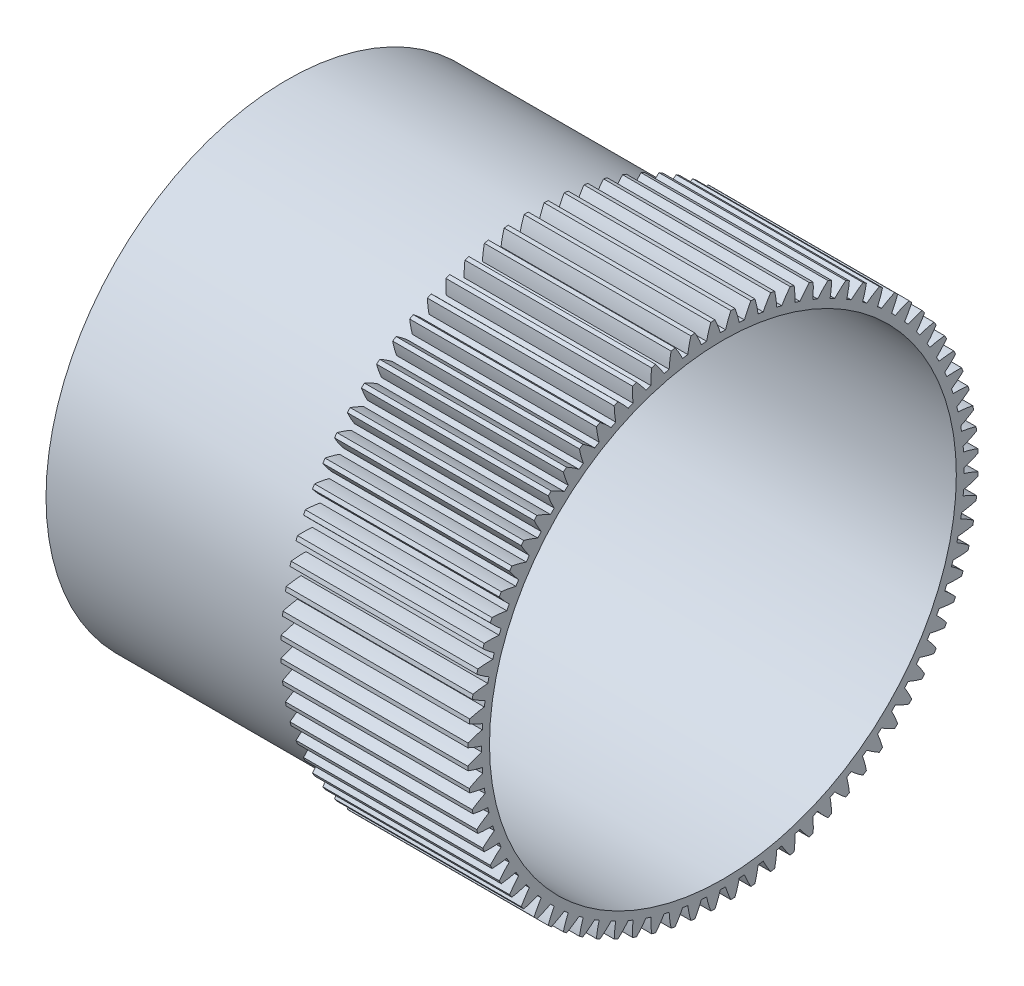
SolidWorks part; units mm, degrees
ref_plane "Plane1" through (0, 0, 0) normal (0, 0, 1) x (1, 0, 0)
ref_plane "Plane2" through (0, 0, 0) normal (0, 1, 0) x (1, 0, 0)
ref_plane "Plane3" through (0, 0, 0) normal (1, 0, 0) x (0, 0, -1)
other "Configuration Table"
sketch "HoldingSke" plane through (0, 0, 0) normal (0, 1, 0) x (1, 0, 0)
  line L0 (0, 0) -> (0.3473, -1.9696)
  line L1 (-15, 0) -> (100, 0) construction
  line L2 (0, 0) -> (-2.1039, 2.3779)
  line L3 (0, 0) -> (-11.863, 4.5341)
  line L4 (0, 0) -> (1.4996, 8.5048)
  line L5 (0, 0) -> (-46.8476, -17.4728)
  line L6 (0, 0) -> (-2.8599, -1.9296)
  line L7 (-2.1039, 2.3779) -> (8.6589, 51.2073)
  line L8 (-76.2, 54.61) -> (-76.1, 54.61)
  line L9 (-71.009, 38.7566) -> (-53.1078, 45.2721)
  line L10 (-76.2, 71.12) -> (104.1128, 71.12)
  line L11 (0, 0) -> (-3.45, 0)
  line L12 (-76.2, 101.6) -> (-76.181, 101.6)
  line L13 (24.9733, 27.94) -> (52.9518, 28.4284)
  line L14 (24.9733, 27.94) -> (24.9743, 27.94)
  line L15 (24.9733, 27.94) -> (100.4006, 29.5858)
  line L16 (-63.627, -0.5) -> (-12.827, -0.5)
  circle A0 centre (0, 0) radius 0.5
  circle A1 centre (0, 0) radius 19.374
  circle A2 centre (0, 0) radius 37.5
  circle A3 centre (0, 0) radius 0.5
  dimension "MHD" = 38.748
  dimension "Hub_dia" = 75
  dimension "Bore" = 1
  dimension "MBD" = 1
  dimension "Num_teeth" = 80
  dimension "Pitch" = 2
  dimension "Overall_len" = 50
  dimension "Show_teeth" = 80
  dimension "Thickness" = 3.45
  dimension "OAL" = 50.0015
  dimension "T_dim" = 0.1
  dimension "Ap" = 20
  dimension "H" = 19.05
  dimension "Pitch_radius" = 180.3128
  dimension "Width" = 3.45
  dimension "Backlash" = 0.019
  dimension "Addendum_fac" = 1
  dimension "Dedendum_fac" = 1.25
  dimension "Clearance_fac" = 0.25
  dimension "Dedendum_add" = 0.001
  dimension "Module" = 0.5
sketch "BasProSke" plane through (0, 0, 0) normal (0, 1, 0) x (1, 0, 0)
  line L0 (-10, 0) -> (60, 0) construction
  line L1 (0, 0) -> (0, 20.5)
  line L2 (0, 0) -> (15, 0)
  line L3 (15, 0) -> (15, 20.5)
  line L4 (15, 20.5) -> (0, 20.5)
  dimension "Thickness" = 15
  dimension "Diameter" = 41
revolve "Base-Revolve" add sketch "BasProSke" angle 360 about L0
sketch "TooCutSke" plane through (0, 0, 0) normal (1, 0, 0) x (0, 0, -1)
  line L1 (0, 0) -> (0, 107) construction
  line L2 (0, 0) -> (-0.4259, 19.9955) construction
  line L3 (0, 0) -> (-1.5701, 39.9627) construction
  line L4 (-0.4259, 19.9955) -> (-0.7851, 19.9814) construction
  arc A0 (0.2101, 19.3729) -> (-0.2101, 19.3729) centre (0, 0) ccw
  arc A1 (0.6519, 20.515) -> (-0.6519, 20.515) centre (0, 0) ccw
  circle A2 centre (0, 0) radius 20 construction
  circle A3 centre (0, 0) radius 18.7939 construction
  arc A4 (-0.2101, 19.3729) -> (-0.6519, 20.515) centre (-7.8705, 17.0665) ccw
  arc A5 (0.6519, 20.515) -> (0.2101, 19.3729) centre (7.8705, 17.0665) ccw
  dimension "Root_dia" = 38.748
  dimension "Overcut_dia" = 41.0508
  dimension "Pitch_dia" = 40
  dimension "Base_dia" = 37.5877
  dimension "Flank_rad" = 8
  dimension "Half_ang" = 2.25
  dimension "Half_CT" = 0.3594
extrude "ToothCut" cut sketch "TooCutSke" along normal through all
fillet "Breaks" [suppressed] radius 0.01
fillet "RootFillets" [suppressed] radius 0.126
pattern_circular "TeethCuts" count 80 every 4.5 about axis through (-10, 0, 0) along (1, 0, 0) of "ToothCut", "RootFillets", "Breaks"
sketch "HubNeaOneSke" plane through (0, 0, 0) normal (-1, 0, 0) x (0, 0, 1)
  circle A0 centre (0, 0) radius 19.374
  dimension "Diameter" = 38.748
extrude "HubNearOne" [suppressed] add sketch "HubNeaOneSke" along normal blind 35.0015
sketch "HubNeaBotSke" plane through (0, 0, 0) normal (-1, 0, 0) x (0, 0, 1)
  circle A0 centre (0, 0) radius 19.374
  dimension "Diameter" = 38.748
extrude "HubNearBoth" [suppressed] add sketch "HubNeaBotSke" along normal blind 17.5008
ref_plane "FarPln" through (15, 0, 0) normal (1, 0, 0) x (0, 0, -1)
sketch "HubFarSke" plane through (15, 0, 0) normal (1, 0, 0) x (0, 0, -1)
  circle A0 centre (0, 0) radius 19.374
  dimension "Diameter" = 38.748
extrude "HubFar" [suppressed] add sketch "HubFarSke" along normal blind 17.5008
sketch "BorSke" plane through (0, 0, 0) normal (1, 0, 0) x (0, 0, -1)
  circle A0 centre (0, 0) radius 0.5
  dimension "Diameter" = 1
extrude "Bore" cut sketch "BorSke" along normal mid plane 100.003
sketch "KeySke" plane through (0, 0, 0) normal (1, 0, 0) x (0, 0, -1)
  line L0 (-0.05, 0) -> (-0.05, 0.6)
  line L1 (-0.05, 0.6) -> (0.05, 0.6)
  line L2 (0.05, 0.6) -> (0.05, 0)
  line L3 (0, 0) -> (0, 34) construction
  line L4 (-0.05, 0) -> (0.05, 0)
  dimension "Offset" = 0.6
  dimension "Width" = 0.1
extrude "Keyway" [suppressed] cut sketch "KeySke" along normal mid plane 100.003
pattern_circular "Keyway2" [suppressed] count 2 every 90 about axis through (-10, 0, 0) along (1, 0, 0)
sketch "Sketch1" plane through (15, 0, 0) normal (1, 0, 0) x (0, 0, -1)
  circle A0 centre (0, 0) radius 18.75
  dimension "D1" = 37.5
extrude "Cut-Extrude1" cut sketch "Sketch1" against normal through all
sketch "Sketch4" plane through (0, 0, 0) normal (-1, 0, 0) x (0, 0, 1)
  circle A0 centre (0, 0) radius 18.75
  circle A1 centre (0, 0) radius 19.374
  arc A2 (17.3567, 8.6079) -> (17.1659, 8.9823) centre (0, 0) ccw construction
  circle A3 centre (0, 0) radius 18.75 construction
extrude "Boss-Extrude5" add sketch "Sketch4" along normal blind 20
sketch "Sketch5" plane through (-20, 0, 0) normal (-1, 0, 0) x (0, 0, 1)
  circle A0 centre (0, 0) radius 18.75
  circle A1 centre (0, 0) radius 18.75 construction
extrude "Boss-Extrude6" add sketch "Sketch5" against normal blind 1
sketch "Sketch6" plane through (-20, 0, 0) normal (-1, 0, 0) x (0, 0, 1)
  circle A0 centre (0, 0) radius 2.45
  dimension "D1" = 4.9
extrude "Boss-Extrude7" add sketch "Sketch6" along normal blind 10
equation "' \"Module@HoldingSke\" = 6.35"
equation "' \"Num_teeth@HoldingSke\" = 12"
equation "' \"Ap@HoldingSke\" =  20"
equation "' \"Ap@HoldingSke\" = 20"
equation "' \"Width@HoldingSke\" = 0.5 * 25.4"
equation "' \"Hub_dia@HoldingSke\"= 1 * 25.4"
equation "' \"Hub_dia@HoldingSke\" = 1 * 25.4"
equation "' \"Overall_len@HoldingSke\" = 1.0 * 25.4"
equation "' \"Bore@HoldingSke\" = 0.75 * 25.4"
equation "' \"T_dim@HoldingSke\" = 0.1 * 25.4"
equation "' \"Width@KeySke\" = 0.25 * 25.4"
equation "' \"Show_teeth@HoldingSke\" = 13"
equation "' \"Backlash@HoldingSke\" = 0.009 * 25.4"
equation "' \"Addendum_fac@HoldingSke\" = 1.0"
equation "' \"Dedendum_fac@HoldingSke\" = 1.25"
equation "' \"Dedendum_add@HoldingSke\" = 0.00005 * 25.4"
equation "' \"Clearance_fac@HoldingSke\" = 0.25"
equation "\"Pitch@HoldingSke\" = 1 / \"Module@HoldingSke\""
equation "\"Overcut_dia@TooCutSke\" = (\"Num_teeth@HoldingSke\" + 2 * \"Addendum_fac@HoldingSke\") / \"Pitch@HoldingSke\" + 0.002 * 25.4"
equation "\"Pitch_dia@TooCutSke\" = \"Num_teeth@HoldingSke\" / \"Pitch@HoldingSke\""
equation "\"Base_dia@TooCutSke\" = \"Num_teeth@HoldingSke\" / \"Pitch@HoldingSke\" * cos((\"Ap@HoldingSke\"  * 3.14159265 / 180))"
equation "\"Root_dia@TooCutSke\" = (\"Num_teeth@HoldingSke\" + 2) / \"Pitch@HoldingSke\" - 2 * (\"Addendum_fac@HoldingSke\" + \"Dedendum_fac@HoldingSke\") / \"Pitch@HoldingSke\" - \"Dedendum_add@HoldingSke\" * 2"
equation "\"Half_ang@TooCutSke\" = 180 / \"Num_teeth@HoldingSke\""
equation "\"Half_CT@TooCutSke\" = \"Num_teeth@HoldingSke\" / \"Pitch@HoldingSke\" * sin((3.14159265 / 2 / \"Num_teeth@HoldingSke\")) / 2 - 7 * \"Backlash@HoldingSke\" / 4"
equation "\"Flank_rad@TooCutSke\" = \"Num_teeth@HoldingSke\" / \"Pitch@HoldingSke\" / 5"
equation "\"Radius@RootFillets\" = \"Clearance_fac@HoldingSke\" / \"Pitch@HoldingSke\" + \"Dedendum_add@HoldingSke\""
equation "\"Break_rad@Breaks\" = 0.02 / \"Pitch@HoldingSke\""
equation "\"Thickness@HoldingSke\" = \"Width@HoldingSke\""
equation "\"OAL@HoldingSke\" = \"Thickness@HoldingSke\""
equation "\"MHD@HoldingSke\" = (\"Num_teeth@HoldingSke\" + 2) / \"Pitch@HoldingSke\" - 2 * (\"Addendum_fac@HoldingSke\" + \"Dedendum_fac@HoldingSke\")  / \"Pitch@HoldingSke\" - \"Dedendum_add@HoldingSke\" * 2"
equation "\"MBD@HoldingSke\" = (\"Num_teeth@HoldingSke\" + 2) / \"Pitch@HoldingSke\" - 2 * (\"Addendum_fac@HoldingSke\" + \"Dedendum_fac@HoldingSke\")  / \"Pitch@HoldingSke\" - \"Dedendum_add@HoldingSke\" * 2 - 0.002 * 25.4"
equation "\"MHD@HoldingSke\" = ((sgn( \"MHD@HoldingSke\" - \"Hub_dia@HoldingSke\" )-1)*( \"MHD@HoldingSke\" - \"Hub_dia@HoldingSke\" ))/-2+ \"Hub_dia@HoldingSke\""
equation "\"MBD@HoldingSke\" = ((sgn( \"MBD@HoldingSke\" - \"Bore@HoldingSke\" )-1)*( \"MBD@HoldingSke\" - \"Bore@HoldingSke\" ))/-2+ \"Bore@HoldingSke\""
equation "\"OAL@HoldingSke\" = ((sgn( \"OAL@HoldingSke\" - \"Overall_len@HoldingSke\" )+1)*( \"OAL@HoldingSke\" - \"Overall_len@HoldingSke\" ))/2 + \"Overall_len@HoldingSke\" + 0.000002 * 25.4"
equation "\"Num_teeth@TeethCuts\" = int( \"Show_teeth@HoldingSke\" ) + 1"
equation "\"Num_teeth@TeethCuts\" = ((sgn( \"Num_teeth@TeethCuts\" - \"Num_teeth@HoldingSke\" )-1)*( \"Num_teeth@TeethCuts\" - \"Num_teeth@HoldingSke\" ))/-2+ \"Num_teeth@HoldingSke\""
equation "\"Num_teeth@TeethCuts\" = ((sgn( \"Num_teeth@TeethCuts\" - 2.0)+1)*( \"Num_teeth@TeethCuts\" - 2.0))/2 +2.0"
equation "\"Angle@TeethCuts\" = 360.0 / \"Num_teeth@HoldingSke\""
equation "\"Diameter@BasProSke\" = (\"Num_teeth@HoldingSke\" + 2 * \"Addendum_fac@HoldingSke\") / \"Pitch@HoldingSke\""
equation "' \"Fillet_rad@BasProSke\" =  \"Thickness@HoldingSke\" * 0.05"
equation "' \"Fillet_rad@BasProSke\" = \"Thickness@HoldingSke\" * 0.05"
equation "\"MHD@HoldingSke\" = ((sgn( \"MHD@HoldingSke\" - \"Root_dia@TooCutSke\" )-1)*( \"MHD@HoldingSke\" - \"Root_dia@TooCutSke\" ))/-2+ \"Root_dia@TooCutSke\""
equation "\"Diameter@HubNeaOneSke\" = \"MHD@HoldingSke\""
equation "\"Length@HubNearOne\" = \"OAL@HoldingSke\" - \"Thickness@BasProSke\""
equation "\"Diameter@HubNeaBotSke\" = \"MHD@HoldingSke\""
equation "\"Length@HubNearBoth\" = ( \"OAL@HoldingSke\" - \"Thickness@BasProSke\" ) / 2.0"
equation "\"Thickness@FarPln\" = \"Thickness@BasProSke\""
equation "\"Diameter@HubFarSke\" = \"MHD@HoldingSke\""
equation "\"Length@HubFar\" = ( \"OAL@HoldingSke\" - \"Thickness@BasProSke\" ) / 2.0"
equation "\"Diameter@BorSke\" = \"MBD@HoldingSke\""
equation "\"D1@Bore\" = \"OAL@HoldingSke\" * 2.0"
equation "\"D1@Keyway\" = \"OAL@HoldingSke\" * 2.0"
equation "\"Offset@KeySke\" = \"T_dim@HoldingSke\" + \"MBD@HoldingSke\" / 2.0"
